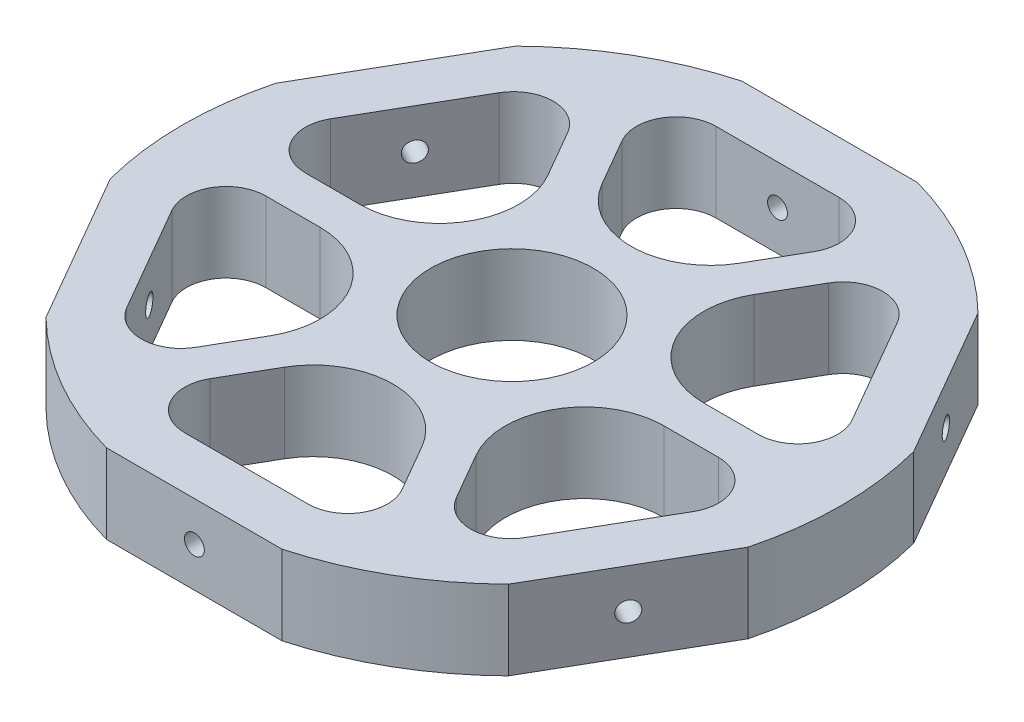
SolidWorks part; units mm, degrees
ref_plane "Front Plane" through (0, 0, 0) normal (0, 0, 1) x (1, 0, 0)
ref_plane "Top Plane" through (0, 0, 0) normal (0, 1, 0) x (1, 0, 0)
ref_plane "Right Plane" through (0, 0, 0) normal (1, 0, 0) x (0, 0, -1)
sketch "Sketch2" plane through (0, 0, 0) normal (0, 1, 0) x (1, 0, 0)
  line L0 (0, 0) -> (-41.5, 71.8801) construction
  line L1 (22.1133, 80) -> (-22.1133, 80)
  line L2 (-58.2254, 59.1507) -> (-80.3387, 20.8493)
  line L3 (-80.3387, -20.8493) -> (-58.2254, -59.1507)
  line L4 (-22.1133, -80) -> (22.1133, -80)
  line L5 (58.2254, -59.1507) -> (80.3387, -20.8493)
  line L6 (80.3387, 20.8493) -> (58.2254, 59.1507)
  line L7 (0, 0) -> (41.5, 71.8801) construction
  line L8 (-41.5, 71.8801) -> (41.5, 71.8801) construction
  line L9 (-15.5192, 66.8801) -> (15.5192, 66.8801)
  line L10 (17.3205, 40) -> (24.1795, 51.8801)
  line L11 (-17.3205, 40) -> (-24.1795, 51.8801)
  line L12 (0, 10) -> (32.8397, 66.8801) construction
  line L13 (0, 10) -> (-32.8397, 66.8801) construction
  line L14 (-32.8397, 66.8801) -> (32.8397, 66.8801) construction
  line L15 (50.1603, 46.8801) -> (65.6795, 20)
  line L16 (43.3013, 5) -> (57.0192, 5)
  line L17 (25.9808, 35) -> (32.8397, 46.8801)
  line L18 (65.6795, -20) -> (50.1603, -46.8801)
  line L19 (25.9808, -35) -> (32.8397, -46.8801)
  line L20 (43.3013, -5) -> (57.0192, -5)
  line L21 (15.5192, -66.8801) -> (-15.5192, -66.8801)
  line L22 (-17.3205, -40) -> (-24.1795, -51.8801)
  line L23 (17.3205, -40) -> (24.1795, -51.8801)
  line L24 (-50.1603, -46.8801) -> (-65.6795, -20)
  line L25 (-43.3013, -5) -> (-57.0192, -5)
  line L26 (-25.9808, -35) -> (-32.8397, -46.8801)
  line L27 (-65.6795, 20) -> (-50.1603, 46.8801)
  line L28 (-25.9808, 35) -> (-32.8397, 46.8801)
  line L29 (-43.3013, 5) -> (-57.0192, 5)
  arc A0 (-80.3387, 20.8493) -> (-80.3387, -20.8493) centre (0, 0) ccw
  circle A1 centre (0, 0) radius 80 construction
  arc A2 (-22.1133, 80) -> (-58.2254, 59.1507) centre (0, 0) ccw
  arc A3 (58.2254, 59.1507) -> (22.1133, 80) centre (0, 0) ccw
  arc A4 (80.3387, -20.8493) -> (80.3387, 20.8493) centre (0, 0) ccw
  arc A5 (22.1133, -80) -> (58.2254, -59.1507) centre (0, 0) ccw
  arc A6 (-58.2254, -59.1507) -> (-22.1133, -80) centre (0, 0) ccw
  circle A7 centre (0, 0) radius 20.5
  arc A8 (17.3205, 40) -> (-17.3205, 40) centre (0, 50) cw
  arc A9 (24.1795, 51.8801) -> (15.5192, 66.8801) centre (15.5192, 56.8801) ccw
  arc A10 (-15.5192, 66.8801) -> (-24.1795, 51.8801) centre (-15.5192, 56.8801) ccw
  arc A11 (50.1603, 46.8801) -> (32.8397, 46.8801) centre (41.5, 41.8801) ccw
  arc A12 (57.0192, 5) -> (65.6795, 20) centre (57.0192, 15) ccw
  arc A13 (43.3013, 5) -> (25.9808, 35) centre (43.3013, 25) cw
  arc A14 (65.6795, -20) -> (57.0192, -5) centre (57.0192, -15) ccw
  arc A15 (32.8397, -46.8801) -> (50.1603, -46.8801) centre (41.5, -41.8801) ccw
  arc A16 (25.9808, -35) -> (43.3013, -5) centre (43.3013, -25) cw
  arc A17 (15.5192, -66.8801) -> (24.1795, -51.8801) centre (15.5192, -56.8801) ccw
  arc A18 (-24.1795, -51.8801) -> (-15.5192, -66.8801) centre (-15.5192, -56.8801) ccw
  arc A19 (-17.3205, -40) -> (17.3205, -40) centre (0, -50) cw
  arc A20 (-50.1603, -46.8801) -> (-32.8397, -46.8801) centre (-41.5, -41.8801) ccw
  arc A21 (-57.0192, -5) -> (-65.6795, -20) centre (-57.0192, -15) ccw
  arc A22 (-43.3013, -5) -> (-25.9808, -35) centre (-43.3013, -25) cw
  arc A23 (-65.6795, 20) -> (-57.0192, 5) centre (-57.0192, 15) ccw
  arc A24 (-32.8397, 46.8801) -> (-50.1603, 46.8801) centre (-41.5, 41.8801) ccw
  arc A25 (-25.9808, 35) -> (-43.3013, 5) centre (-43.3013, 25) cw
  point P78 (0, 0)
  dimension "D1" = 160
  dimension "D2" = 83
  dimension "D4" = 20
  dimension "D5" = 10
  dimension "D3" = 5
  dimension "D6" = 6
extrude "Boss-Extrude1" add sketch "Sketch2" along normal blind 20
sketch "Sketch3" plane through (0, 0, 80) normal (0, 0, 1) x (1, 0, 0)
  line L0 (-22.1133, 0) -> (22.1133, 0) construction
  circle A0 centre (0, 10) radius 2.5
  dimension "D1" = 5
  dimension "D2" = 10
extrude "Cut-Extrude1" cut sketch "Sketch3" against normal blind 20
pattern_circular "CirPattern1" count 6 over 360 about axis through (0, 20, 0) along (0, 1, 0) of "Cut-Extrude1"
